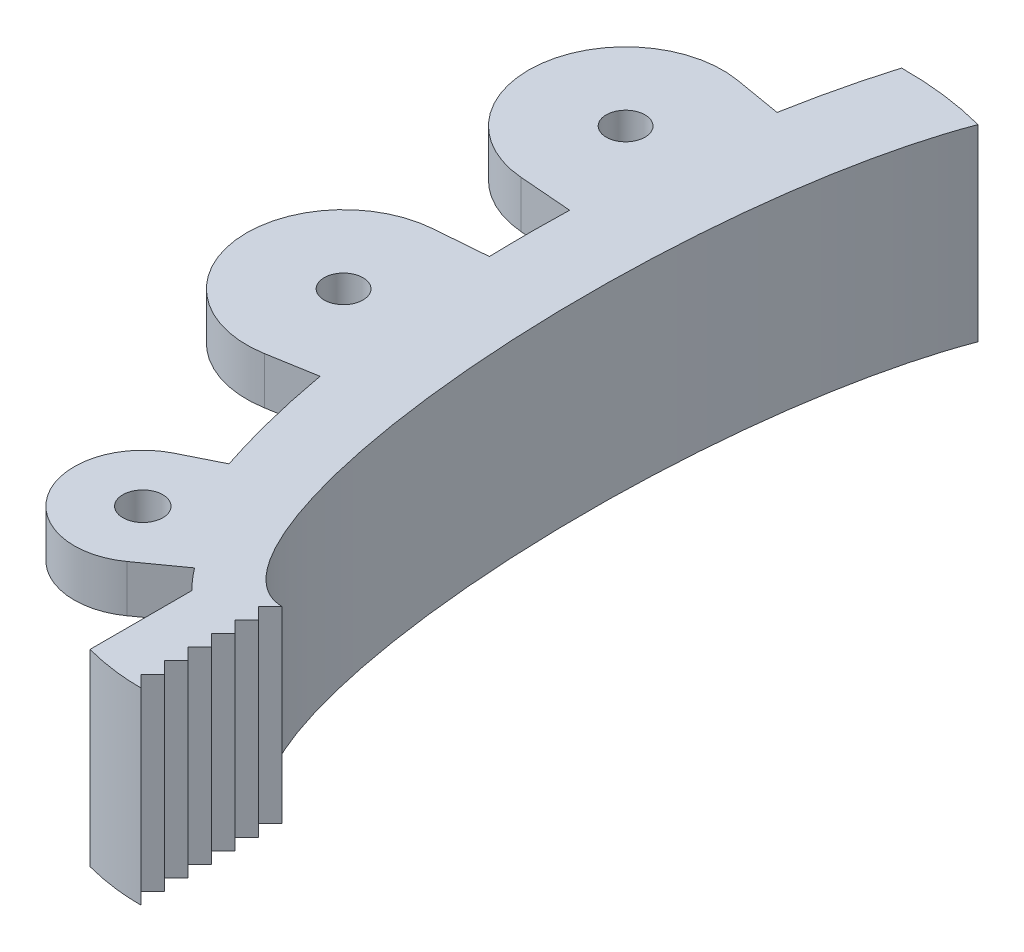
SolidWorks part; units mm, degrees
ref_plane "Спереди" through (0, 0, 0) normal (0, 0, 1) x (1, 0, 0)
ref_plane "Сверху" through (0, 0, 0) normal (0, 1, 0) x (1, 0, 0)
ref_plane "Справа" through (0, 0, 0) normal (1, 0, 0) x (0, 0, -1)
sketch "Эскиз1" plane through (0, 0, 0) normal (0, 1, 0) x (1, 0, 0)
  line L0 (0, -50) -> (0, -43) construction
  line L1 (0, 43) -> (0, 50) construction
  line L2 (0, 0) -> (-19.6172, -53.8979) construction
  line L3 (0, 0) -> (-42.6769, 24.6395) construction
  line L4 (0, 0) -> (-61.6064, -35.5685) construction
  line L5 (0, 0) -> (-46.6238, 0) construction
  line L6 (-9.8992, -41.278) -> (-5.8609, -38.382)
  line L7 (-15.8943, -31.3136) -> (-12.7538, -29.7532)
  line L8 (-19.3819, -20.1257) -> (-15.3331, -19.4333)
  line L9 (-21.4293, -3.7686) -> (-16.9511, -3.411)
  line L10 (-21.4293, 3.7686) -> (-16.9511, 3.411)
  line L11 (-19.3819, 20.1257) -> (-15.3331, 19.4333)
  circle A0 centre (-13.2986, -36.5376) radius 1.7
  arc A1 (-9.9103, 27.829) -> (-13.3088, 27.9983) centre (-13, 0) ccw
  circle A2 centre (-20.7726, 11.9931) radius 1.65
  circle A3 centre (-20.7726, -11.9931) radius 1.65
  arc A4 (-19.3819, 20.1257) -> (-21.4293, 3.7686) centre (-20.7726, 11.9931) ccw
  arc A5 (-21.4293, -3.7686) -> (-19.3819, -20.1257) centre (-20.7726, -11.9931) ccw
  arc A6 (-15.8943, -31.3136) -> (-9.8992, -41.278) centre (-13.2986, -36.5376) ccw
  ellipse E0 centre (0, 0) end of major axis (0, -43) minor radius 13 (-9.9103, 27.829) -> (-5.8609, -38.382) ccw
  ellipse E1 centre (0, 0) end of major axis (0, -50) minor radius 30 (-26.23, 24.2663) -> (0, -50) ccw construction
  ellipse E2 centre (0, 0) end of major axis (0, -46.5) minor radius 21.5 (0, 46.5) -> (0, -46.5) ccw construction
  ellipse E3 centre (0, 0) end of major axis (0, -45) minor radius 17 (-13.3088, 27.9983) -> (-15.3331, 19.4333) ccw
  ellipse E4 centre (0, 0) end of major axis (0, -45) minor radius 17 (-16.9511, 3.411) -> (-16.9511, -3.411) ccw
  ellipse E5 centre (0, 0) end of major axis (0, -45) minor radius 17 (-15.3331, -19.4333) -> (-12.7538, -29.7532) ccw
  dimension "D1" = 43
  dimension "D9" = 60
  dimension "D10" = 3.4
  dimension "D2" = 13
  dimension "D3" = 30
  dimension "D4" = 50
  dimension "D5" = 21.5
  dimension "D6" = 46.5
  dimension "D7" = 20
  dimension "D8" = 120
extrude "Бобышка-Вытянуть1" add sketch "Эскиз1" along normal blind 4
sketch "Эскиз2" plane through (0, 4, 0) normal (0, 1, 0) x (1, 0, 0)
  line L0 (0, -38) -> (0, -50) construction
  line L1 (-5, -49.3276) -> (-5, -40.6552)
  line L2 (0, -48) -> (-1, -47)
  line L3 (0, -48) -> (-1, -48) construction
  line L4 (0, -50) -> (-1, -49)
  line L5 (0, -50) -> (-1, -50) construction
  line L6 (-1, -48) -> (-1, -50) construction
  line L7 (-1, -49) -> (0, -48)
  line L8 (-1, -47) -> (0, -46)
  line L9 (0, -46) -> (-1, -45)
  line L10 (-1, -45) -> (0, -44)
  line L11 (0, -44) -> (-1, -43)
  line L12 (-1, -43) -> (0, -42)
  line L13 (0, -42) -> (-1, -41)
  line L14 (-1, -41) -> (0, -40)
  line L15 (0, -40) -> (-1, -39)
  line L16 (-1, -39) -> (0, -38)
  arc A1 (-10.2762, 27.8672) -> (-5.8937, 27.0832) centre (-13, 0) cw
  ellipse E0 centre (0, -2) end of major axis (0, -43) minor radius 15 (-10.4383, 27.4443) -> (0, -43) ccw construction
  ellipse E1 centre (0, -2) end of major axis (0, -38) minor radius 10 (-5.8937, 27.0832) -> (0, -38) ccw
  ellipse E2 centre (0, -2) end of major axis (0, 46) minor radius 29.976 (-5, -49.3276) -> (0, -50) ccw
  ellipse E4 centre (0, -2) end of major axis (0, -43) minor radius 15 (-10.2762, 27.8672) -> (-5, -40.6552) ccw
  ellipse E5 centre (0, 0) end of major axis (0, -43) minor radius 13 (-9.9103, 27.829) -> (-5.8609, -38.382) ccw construction
  dimension "D3" = 5
  dimension "D7" = 6
  dimension "D1" = 36
  dimension "D2" = 5
  dimension "D4" = 10
  dimension "D5" = 48
  dimension "D6" = 5
extrude "Бобышка-Вытянуть2" add sketch "Эскиз2" against normal blind 16
